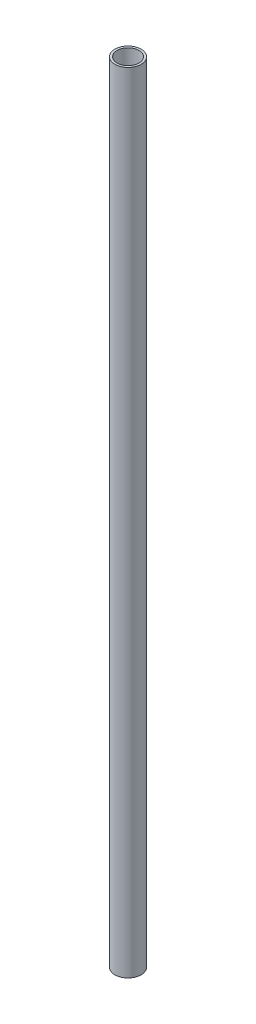
SolidWorks part; units mm, degrees
material "Thornel VCB-20 碳布"
ref_plane "前视基准面" through (0, 0, 0) normal (0, 0, 1) x (1, 0, 0)
ref_plane "上视基准面" through (0, 0, 0) normal (0, 1, 0) x (1, 0, 0)
ref_plane "右视基准面" through (0, 0, 0) normal (1, 0, 0) x (0, 0, -1)
other "Configuration Table"
sketch "草图1" plane through (0, 0, 0) normal (0, 1, 0) x (1, 0, 0)
  circle A0 centre (0, 0) radius 2.5
  circle A1 centre (0, 0) radius 3
  dimension "D1" = 6
  dimension "D2" = 5
extrude "凸台-拉伸1" add sketch "草图1" along normal blind 180
equation "\"R1\"= 5"
equation "\"R2\"= 6"
equation "\"h\"= 180"
equation "\"D1@草图1\"=\"R2\""
equation "\"D2@草图1\"=\"R1\""
equation "\"D1@凸台-拉伸1\"=\"h\""
